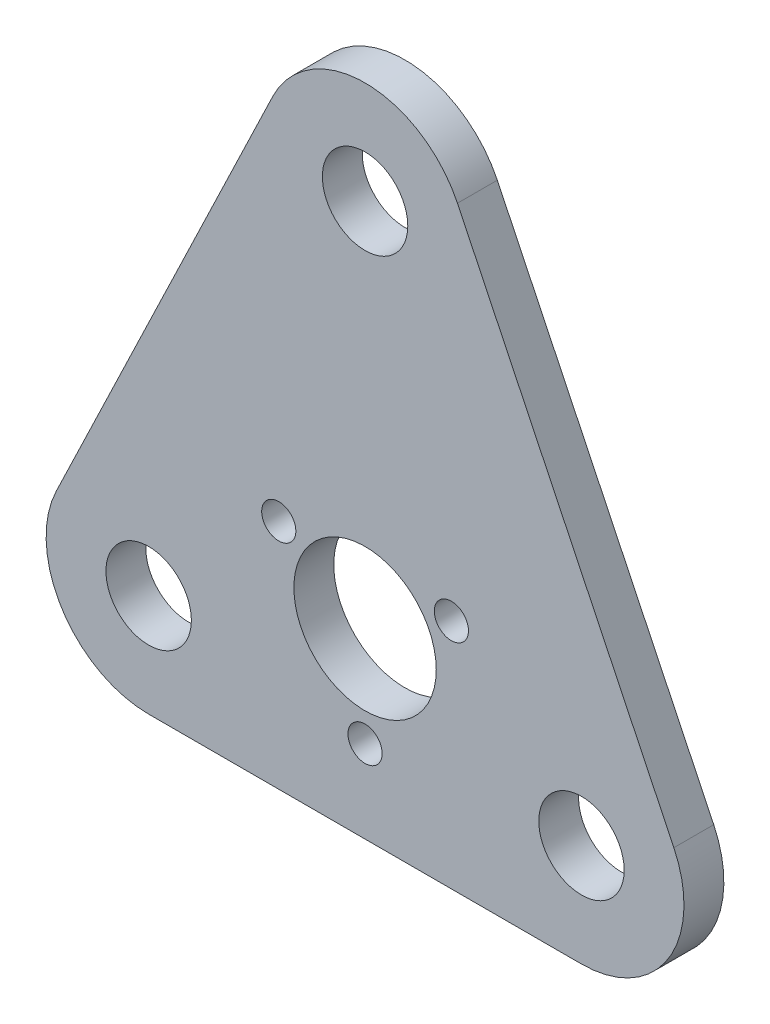
SolidWorks part; units mm, degrees
material "AISI 1020"
ref_plane "Front Plane" through (0, 0, 0) normal (0, 0, 1) x (1, 0, 0)
ref_plane "Top Plane" through (0, 0, 0) normal (0, 1, 0) x (1, 0, 0)
ref_plane "Right Plane" through (0, 0, 0) normal (1, 0, 0) x (0, 0, -1)
sketch "Sketch1" plane through (0, 0, 0) normal (0, 0, 1) x (1, 0, 0)
  line L0 (-16.221, 86.8025) -> (-54.221, 7.8025)
  line L1 (-38, -18) -> (38, -18)
  line L2 (16.221, 86.8025) -> (54.221, 7.8025)
  line L3 (0, 114.8664) -> (0, -39.97) construction
  line L4 (-29.6468, 14) -> (32.3357, 14) construction
  line L5 (0, 14) -> (-25.6578, 28.8135) construction
  line L6 (0, 14) -> (24.728, 28.2767) construction
  arc A0 (-54.221, 7.8025) -> (-38, -18) centre (-38, 0) ccw
  arc A1 (38, -18) -> (54.221, 7.8025) centre (38, 0) ccw
  arc A2 (16.221, 86.8025) -> (-16.221, 86.8025) centre (0, 79) ccw
  circle A3 centre (-38, 0) radius 7.5
  circle A4 centre (38, 0) radius 7.5
  circle A5 centre (0, 79) radius 7.5
  circle A6 centre (0, 14) radius 12.5
  circle A8 centre (0, 14) radius 17.5 construction
  circle A10 centre (-15.1554, 22.75) radius 3
  circle A11 centre (15.1554, 22.75) radius 3
  circle A12 centre (0, -3.5) radius 3
  point P21 (0, 97)
  dimension "D1" = 18
  dimension "D2" = 15
  dimension "D5" = 25
  dimension "D8" = 35
  dimension "D9" = 30
  dimension "D10" = 6
  dimension "D12" = 6
  dimension "D13" = 6
  dimension "D14" = 25
  dimension "D3" = 76
  dimension "D4" = 38
  dimension "D6" = 32
  dimension "D7" = 115
  dimension "D11" = 30
extrude "Boss-Extrude1" add sketch "Sketch1" along normal mid plane 7
